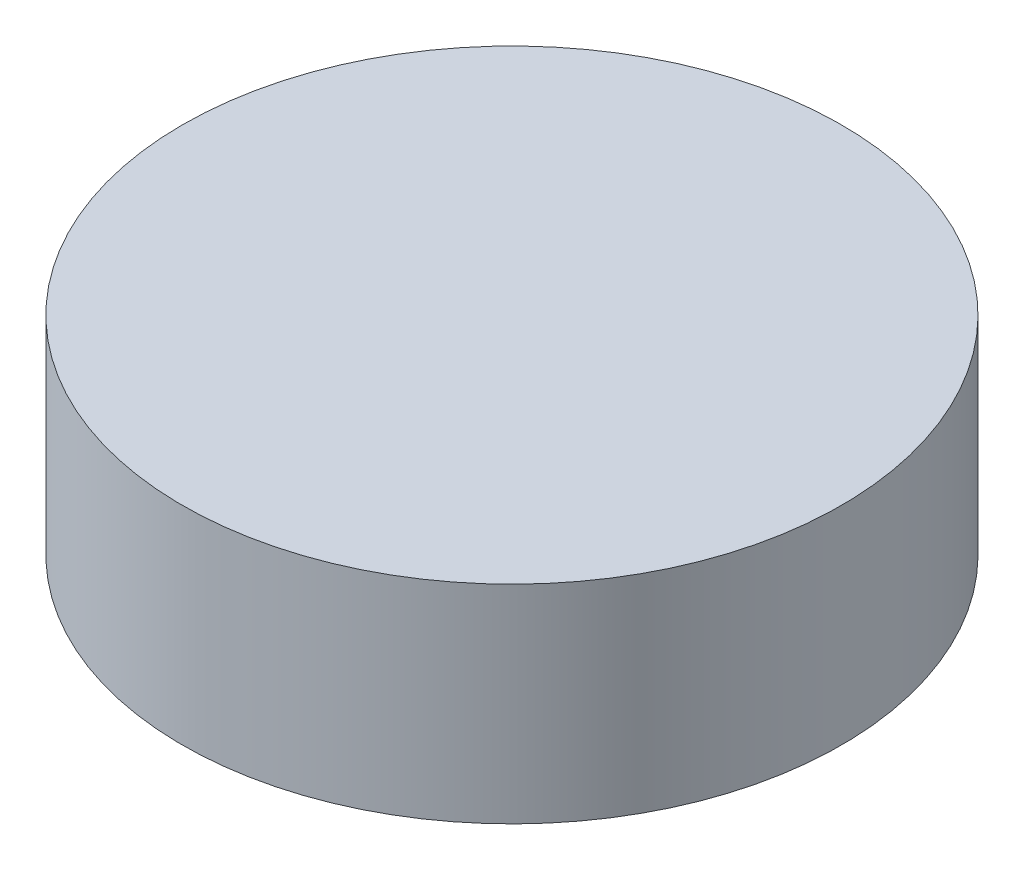
SolidWorks part; units mm, degrees
ref_plane "Front Plane" through (0, 0, 0) normal (0, 0, 1) x (1, 0, 0)
ref_plane "Top Plane" through (0, 0, 0) normal (0, 1, 0) x (1, 0, 0)
ref_plane "Right Plane" through (0, 0, 0) normal (1, 0, 0) x (0, 0, -1)
sketch "Sketch1" plane through (0, 0, 0) normal (0, 0, 1) x (1, 0, 0)
  line L0 (0, 0) -> (-6.35, 0)
  line L1 (-6.35, 0) -> (-6.35, 4)
  line L2 (-6.35, 4) -> (0, 4)
  line L3 (0, 4) -> (0, 0)
  point P3 (0, 0)
  dimension "D1" = 6.35
  dimension "D2" = 4
revolve "Revolve1" add sketch "Sketch1" angle 360 about L3
equation "\"D1@Sketch1\"=12.7/2"
